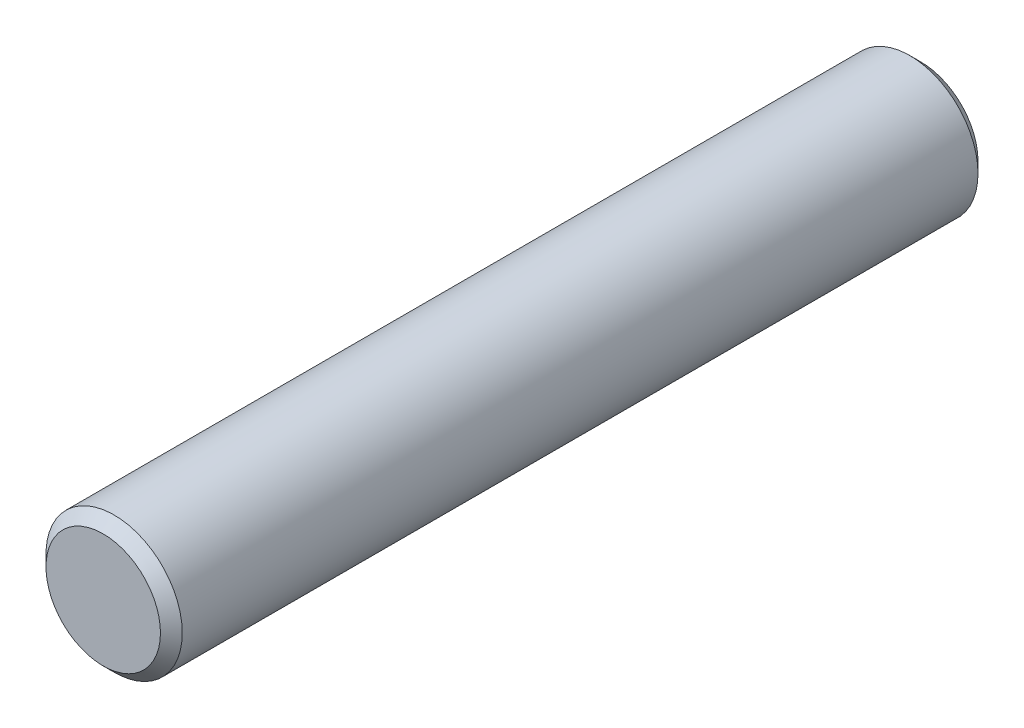
SolidWorks part; units mm, degrees
ref_plane "Front Plane" through (0, 0, 0) normal (0, 0, 1) x (1, 0, 0)
ref_plane "Top Plane" through (0, 0, 0) normal (0, 1, 0) x (1, 0, 0)
ref_plane "Right Plane" through (0, 0, 0) normal (1, 0, 0) x (0, 0, -1)
sketch "Sketch1" plane through (0, 0, 0) normal (0, 0, 1) x (1, 0, 0)
  circle A0 centre (0, 0) radius 2.5
  dimension "D1" = 5
extrude "Boss-Extrude1" add sketch "Sketch1" along normal blind 30
chamfer "Chamfer1" distance 0.4 angle 45 2 edges at (2.5, 0, 0) (2.5, 0, 30)
